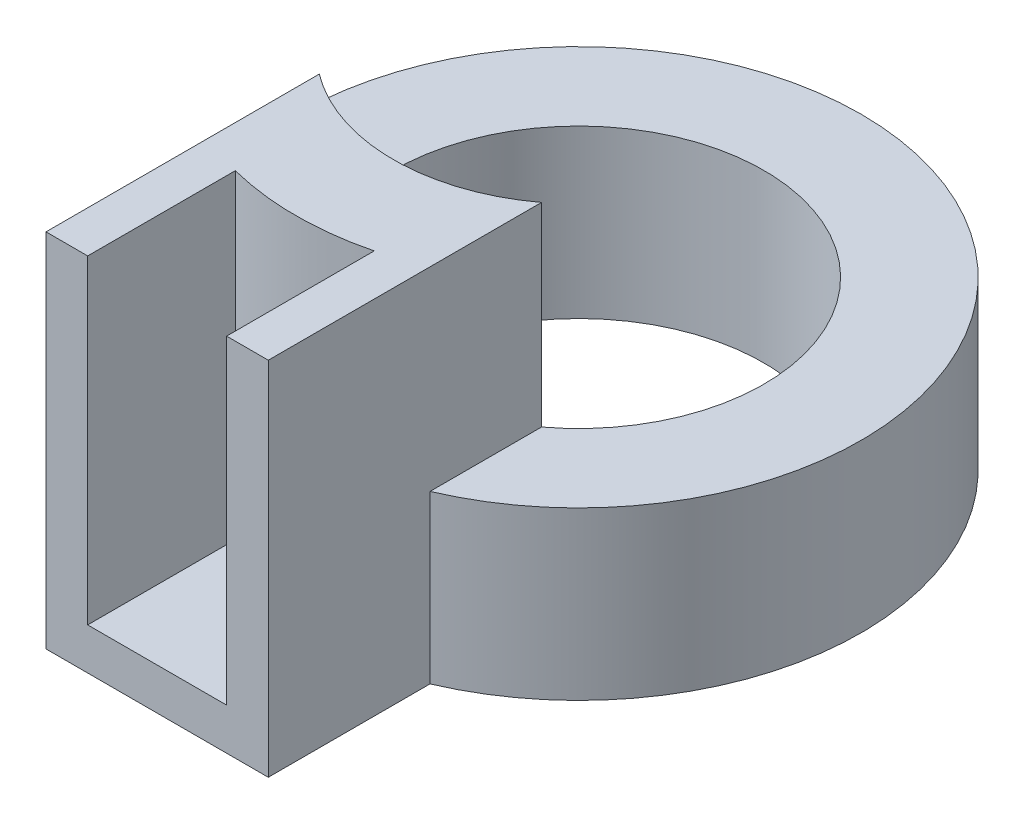
SolidWorks part; units mm, degrees
ref_plane "Front Plane" through (0, 0, 0) normal (0, 0, 1) x (1, 0, 0)
ref_plane "Top Plane" through (0, 0, 0) normal (0, 1, 0) x (1, 0, 0)
ref_plane "Right Plane" through (0, 0, 0) normal (1, 0, 0) x (0, 0, -1)
sketch "Sketch1" plane through (0, 0, 0) normal (0, 1, 0) x (1, 0, 0)
  circle A0 centre (0, 0) radius 13.335
  circle A1 centre (0, 0) radius 20.335
  dimension "D1" = 26.67
  dimension "D2" = 7
extrude "Boss-Extrude1" add sketch "Sketch1" along normal blind 12
ref_plane "Plane1" through (0, 0, 20.335) normal (0, 0, 1) x (1, 0, 0)
sketch "Sketch2" plane through (0, 0, 20.335) normal (0, 0, 1) x (1, 0, 0)
  line L1 (-5, 23) -> (5, 23)
  line L2 (-5, 23) -> (-5, 3)
  line L3 (-5, 3) -> (5, 3)
  line L4 (5, 23) -> (5, 3)
  line L8 (-8, 26) -> (-8, 0)
  line L9 (-8, 0) -> (8, 0)
  line L10 (8, 26) -> (8, 0)
  line L11 (-8, 26) -> (8, 26)
  dimension "D1" = 20
  dimension "D2" = 10
  dimension "D3" = 3
extrude "Boss-Extrude2" add sketch "Sketch2" along normal blind 10 and the other way up to surface other way up to face at (0, 12, 13.335)
sketch "Sketch3" plane through (0, 0, 30.335) normal (0, 0, 1) x (1, 0, 0)
  line L1 (-5, 26) -> (5, 26)
  line L2 (-5, 26) -> (-5, 23)
  line L3 (-5, 23) -> (5, 23)
  line L4 (5, 26) -> (5, 23)
  line L5 (5, 12) -> (5, 3) construction
  line L6 (8, 26) -> (-8, 26) construction
  point P5 (5, 22.0606)
  point P6 (-4.2775, 26.6606)
  point P9 (5, 0)
  point P10 (-4.7263, 24.9771)
  point P11 (-5, 23)
  point P13 (5, 26)
extrude "Cut-Extrude1" cut sketch "Sketch3" against normal up to surface (10.6243 mm away)
sketch "Sketch4" plane through (0, 12, 0) normal (0, 1, 0) x (1, 0, 0)
  line L2 (5, -19.7107) -> (5, -12.3621)
  line L3 (-5, -12.3621) -> (-5, -19.7107)
  line L4 (5, -19.7107) -> (5, -12.3621)
  line L5 (-5, -12.3621) -> (-5, -19.7107)
  arc A2 (-5, -19.7107) -> (5, -19.7107) centre (0, 0) ccw
  arc A3 (-5, -12.3621) -> (5, -12.3621) centre (0, 0) ccw
  arc A4 (-5, -19.7107) -> (5, -19.7107) centre (0, 0) ccw
  arc A5 (-5, -12.3621) -> (5, -12.3621) centre (0, 0) ccw
  dimension "D1" = 0
extrude "Boss-Extrude3" add sketch "Sketch4" along normal up to surface (11 mm away) up to face at (0, 23, 16.4357)
